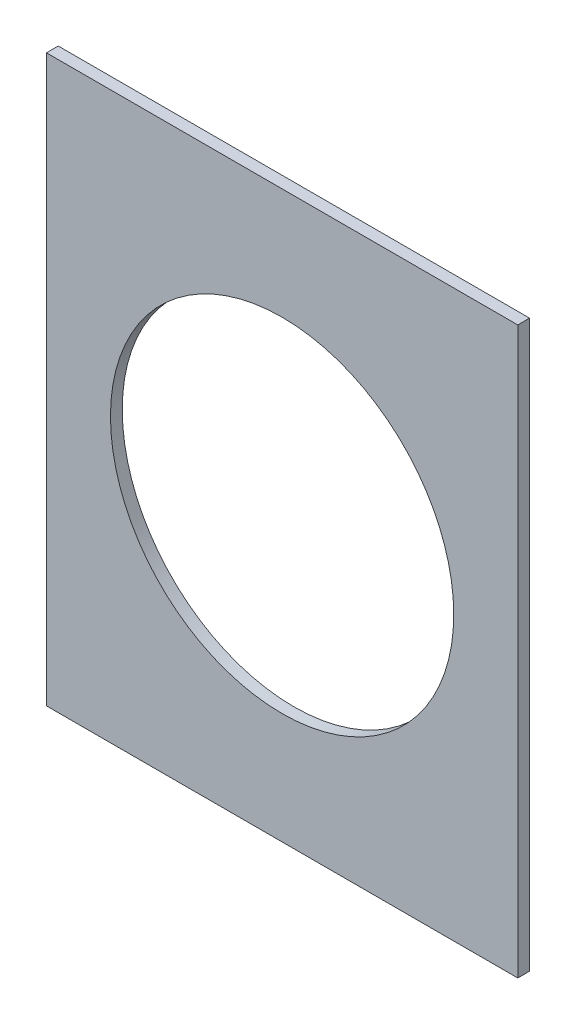
SolidWorks part; units mm, degrees
ref_plane "Plan de face" through (0, 0, 0) normal (0, 0, 1) x (1, 0, 0)
ref_plane "Plan de dessus" through (0, 0, 0) normal (0, 1, 0) x (1, 0, 0)
ref_plane "Plan de droite" through (0, 0, 0) normal (1, 0, 0) x (0, 0, -1)
sketch "Esquisse1" plane through (0, 0, 0) normal (0, 0, 1) x (1, 0, 0)
  line L1 (300, -360) -> (-300, -360)
  line L2 (300, -360) -> (300, 360)
  line L3 (300, 360) -> (-300, 360)
  line L4 (-300, -360) -> (-300, 360)
  line L5 (300, -360) -> (-300, 360) construction
  line L6 (300, 360) -> (-300, -360) construction
  point P0 (0, 0)
  dimension "D1" = 720
  dimension "D2" = 600
extrude "Boss.-Extru.1" add sketch "Esquisse1" along normal blind 15
sketch "Esquisse2" plane through (0, 0, 15) normal (0, 0, 1) x (1, 0, 0)
  circle A0 centre (0, 0) radius 218.5
  dimension "D1" = 437
extrude "Enlèv. mat.-Extru.1" cut sketch "Esquisse2" against normal blind 15
